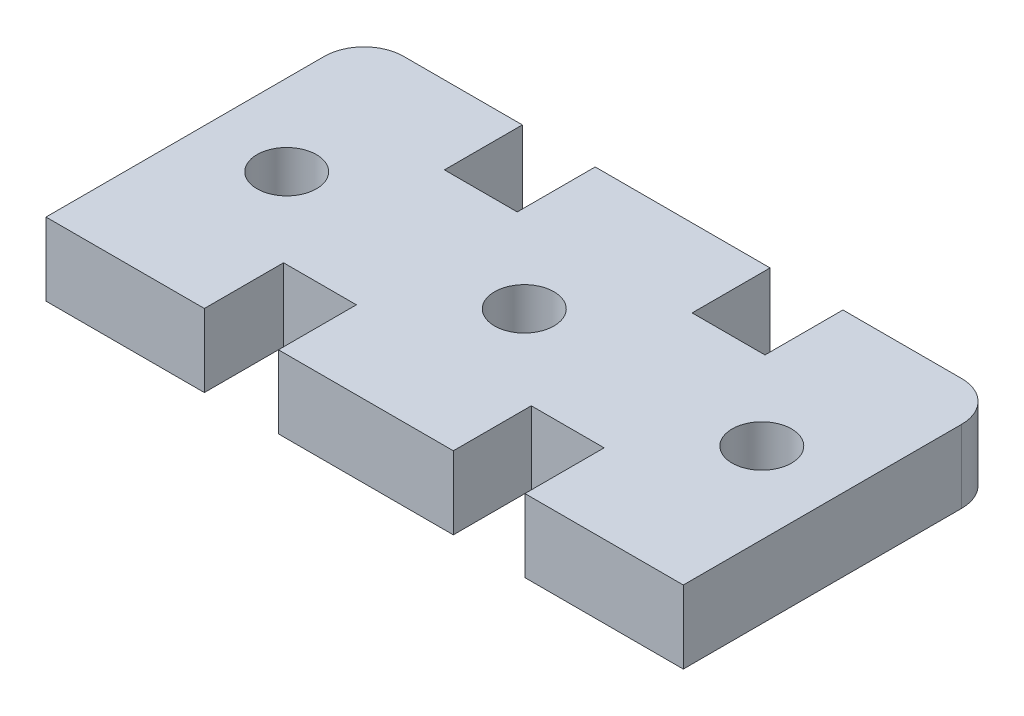
SolidWorks part; units mm, degrees
ref_plane "Front Plane" through (0, 0, 0) normal (0, 0, 1) x (1, 0, 0)
ref_plane "Top Plane" through (0, 0, 0) normal (0, 1, 0) x (1, 0, 0)
ref_plane "Right Plane" through (0, 0, 0) normal (1, 0, 0) x (0, 0, -1)
sketch "Sketch1" plane through (0, 0, 0) normal (0, 1, 0) x (1, 0, 0)
  line L0 (18.896, 0) -> (-7.012, 0) construction
  line L1 (7.012, -12.7) -> (-7.012, -12.7)
  line L2 (7.012, -12.7) -> (7.012, -6.45)
  line L3 (7.012, 12.7) -> (-7.012, 12.7)
  line L4 (-7.012, -12.7) -> (-7.012, -6.45)
  line L5 (7.012, -12.7) -> (-7.012, 12.7) construction
  line L6 (7.012, 12.7) -> (-7.012, -12.7) construction
  line L7 (0, -12.7) -> (0, 12.7) construction
  line L8 (-7.012, 6.45) -> (-7.012, 12.7)
  line L9 (-12.854, -6.45) -> (-7.012, -6.45)
  line L11 (-12.854, 6.45) -> (-7.012, 6.45)
  line L12 (12.854, 6.45) -> (7.012, 6.45)
  line L13 (-12.854, -6.45) -> (-7.012, 6.45) construction
  line L14 (-12.854, 6.45) -> (-7.012, -6.45) construction
  line L15 (12.854, -6.45) -> (7.012, -6.45)
  line L16 (12.854, 6.45) -> (12.854, 12.7)
  line L17 (7.012, 6.45) -> (7.012, 12.7)
  line L18 (-12.854, 6.45) -> (-12.854, 12.7)
  line L19 (25.554, -12.7) -> (12.854, -12.7)
  line L20 (25.554, -12.7) -> (25.554, 12.7)
  line L21 (25.554, 12.7) -> (12.854, 12.7)
  line L22 (12.854, -12.7) -> (12.854, -6.45)
  line L23 (25.554, -12.7) -> (12.854, 12.7) construction
  line L24 (25.554, 12.7) -> (12.854, -12.7) construction
  line L25 (-12.854, -12.7) -> (-12.854, -6.45)
  line L26 (-25.554, -12.7) -> (-12.854, -12.7)
  line L27 (-25.554, -12.7) -> (-25.554, 12.7)
  line L28 (-25.554, 12.7) -> (-12.854, 12.7)
  point P0 (0, 0)
  point P10 (-9.933, 0)
  point P19 (9.933, 0)
  point P20 (19.204, 0)
  dimension "D1" = 14.024
  dimension "D2" = 25.4
  dimension "D3" = 5.842
  dimension "D4" = 12.9
  dimension "D5" = 12.7
extrude "Boss-Extrude1" add sketch "Sketch1" along normal blind 5.842
sketch "Sketch3" plane through (0, 5.842, 0) normal (0, 1, 0) x (1, 0, 0)
  line L0 (25.554, 0) -> (-25.554, 0) construction
  line L3 (25.554, -12.7) -> (25.554, 12.7) construction
  line L4 (-25.554, 12.7) -> (-25.554, -12.7) construction
  line L5 (0, 12.7) -> (0, -12.7) construction
  line L6 (7.012, 12.7) -> (-7.012, 12.7) construction
  line L7 (-7.012, -12.7) -> (7.012, -12.7) construction
  circle A0 centre (0, 0) radius 2.3813
  circle A1 centre (-19.05, 0) radius 2.3813
  circle A2 centre (19.05, 0) radius 2.3813
  dimension "D1" = 4.7625
  dimension "D2" = 4.7625
  dimension "D3" = 19.05
extrude "Cut-Extrude2" cut sketch "Sketch3" against normal through all
fillet "Fillet1" radius 3.175 2 edges at (25.554, 2.921, -12.7) (-25.554, 2.921, -12.7)
sketch "Sketch4" plane through (0, 5.842, 0) normal (0, 1, 0) x (1, 0, 0)
  line L0 (0, 12.7) -> (0, -12.7) construction
  line L1 (-25.554, -12.7) -> (-12.854, -12.7)
  line L2 (-25.554, -12.7) -> (-25.554, -12.8)
  line L3 (-25.554, -12.8) -> (-12.854, -12.8)
  line L4 (-12.854, -12.7) -> (-12.854, -12.8)
  line L5 (7.012, 12.7) -> (-7.012, 12.7) construction
  line L6 (-7.012, -12.7) -> (7.012, -12.7) construction
  line L7 (12.854, -12.7) -> (12.854, -12.8)
  line L8 (25.554, -12.8) -> (12.854, -12.8)
  line L9 (25.554, -12.7) -> (25.554, -12.8)
  line L10 (25.554, -12.7) -> (12.854, -12.7)
  dimension "D1" = 0.1
  dimension "D2" = 12.7
extrude "Boss-Extrude2" add sketch "Sketch4" against normal up to surface (5.842 mm away) up to face at (19.05, 0, -2.3812)
